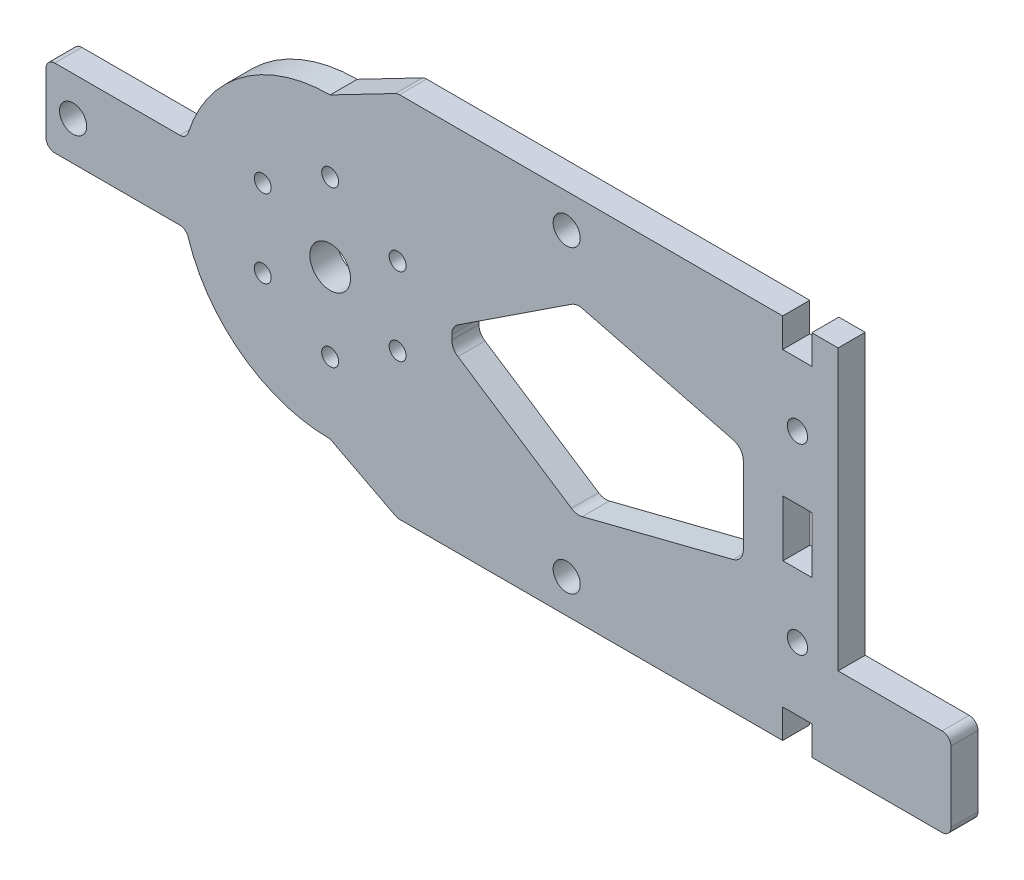
SolidWorks part; units mm, degrees
ref_plane "前视基准面" through (0, 0, 0) normal (0, 0, 1) x (1, 0, 0)
ref_plane "上视基准面" through (0, 0, 0) normal (0, 1, 0) x (1, 0, 0)
ref_plane "右视基准面" through (0, 0, 0) normal (1, 0, 0) x (0, 0, -1)
sketch "草图1" plane through (0, 0, 0) normal (0, 0, 1) x (1, 0, 0)
  line L0 (30.001, 15) -> (30.001, 12) construction
  line L1 (27.8157, 27.15) -> (32.1157, 27.15) construction
  line L2 (32.151, -4.15) -> (27.851, -4.15)
  line L3 (32.151, -4.15) -> (32.151, 4.15)
  line L4 (32.151, 4.15) -> (27.851, 4.15)
  line L5 (27.851, -4.15) -> (27.851, 4.15)
  line L6 (32.151, -4.15) -> (27.851, 4.15) construction
  line L7 (32.151, 4.15) -> (27.851, -4.15) construction
  line L8 (32.1157, 27.15) -> (32.1157, 22.85)
  line L9 (27.8157, 22.85) -> (32.1157, 22.85)
  line L10 (27.8157, 27.15) -> (27.8157, 22.85)
  line L11 (30.001, 0) -> (30.8707, 0) construction
  line L12 (27.8157, -27.15) -> (32.1157, -27.15) construction
  line L13 (30.001, -15) -> (30.001, -12) construction
  line L14 (27.8157, -27.15) -> (27.8157, -22.85)
  line L15 (27.8157, -22.85) -> (32.1157, -22.85)
  line L16 (32.1157, -27.15) -> (32.1157, -22.85)
  line L17 (32.1157, -27.15) -> (36.001, -27.15)
  line L18 (36.001, -27.15) -> (36.001, 27.15) construction
  line L19 (36.001, 27.15) -> (32.1157, 27.15)
  line L23 (-38.999, -22.002) -> (-29.075, -27.15)
  line L25 (-38.999, 22.002) -> (-29.075, 27.15)
  line L29 (27.8157, -27.15) -> (-29.075, -27.15)
  line L30 (-29.075, 27.15) -> (27.8157, 27.15)
  line L31 (-29.075, -27.15) -> (-29.075, 27.15) construction
  line L34 (-48.9583, 5.75) -> (-48.9583, -5.75) construction
  line L38 (-60.2364, 5.75) -> (-80.9583, 5.75)
  line L39 (-80.9583, -5.75) -> (-60.2364, -5.75)
  line L40 (-80.9583, 5.75) -> (-80.9583, -5.75)
  line L41 (36.001, -27.15) -> (52.6592, -27.15)
  line L42 (52.6592, -27.15) -> (52.6592, -14.15)
  line L43 (52.6592, -14.15) -> (36.001, -14.15)
  line L44 (36.001, -14.15) -> (36.001, 27.15)
  line L45 (-4.075, -22.15) -> (30.001, -13.5) construction
  line L46 (30.001, -13.5) -> (30.001, 13.5) construction
  line L47 (30.001, 13.5) -> (-4.075, 22.15) construction
  line L48 (-4.075, 22.15) -> (-29.0397, 5.75) construction
  line L49 (-29.0397, 5.75) -> (-29.0397, -5.75) construction
  line L50 (-29.0397, -5.75) -> (-4.075, -22.15) construction
  line L51 (-21.0397, -1.4336) -> (-2.6278, -13.5289)
  line L52 (-2.6278, -13.5289) -> (22.001, -7.277)
  line L53 (22.001, -7.277) -> (22.001, 7.277)
  line L54 (22.001, 7.277) -> (-2.6278, 13.5289)
  line L55 (-2.6278, 13.5289) -> (-21.0397, 1.4336)
  line L56 (-21.0397, 1.4336) -> (-21.0397, -1.4336)
  circle A0 centre (30.001, 13.5) radius 1.5
  circle A1 centre (30.001, -13.5) radius 1.5
  circle A3 centre (-38.999, 0) radius 3
  circle A6 centre (-38.999, 0) radius 11.5 construction
  circle A7 centre (-38.999, -11.5) radius 1.25
  circle A18 centre (-38.999, 0) radius 22.002 construction
  circle A25 centre (-48.9583, -5.75) radius 1.25
  circle A26 centre (-48.9583, 5.75) radius 1.25
  circle A27 centre (-38.999, 11.5) radius 1.25
  circle A28 centre (-29.0397, 5.75) radius 1.25
  circle A29 centre (-29.0397, -5.75) radius 1.25
  circle A30 centre (-4.075, -22.15) radius 2
  circle A31 centre (-4.075, 22.15) radius 2
  arc A32 (-38.999, -22.002) -> (-60.2364, -5.75) centre (-38.999, 0) cw
  arc A33 (-60.2364, 5.75) -> (-38.999, 22.002) centre (-38.999, 0) cw
  circle A34 centre (-76.9583, 0) radius 2
  point P4 (30.001, 0)
  dimension "D3" = 6
  dimension "D4" = 75
  dimension "D5" = 6
  dimension "D6" = 11.5
  dimension "D7" = 23
  dimension "D8" = 2.5
  dimension "D9" = 25
  dimension "D11" = 5
  dimension "D14" = 4
  dimension "D1" = 8.3
  dimension "D2" = 4.3
  dimension "D10" = 5
  dimension "D12" = 25
  dimension "D13" = 28
  dimension "D15" = 3.8853
  dimension "D16" = 4.3
  dimension "D17" = 13
  dimension "D18" = 8
extrude "凸台-拉伸1" add sketch "草图1" along normal blind 4
fillet "圆角1" radius 1.3 8 edges at (-80.9583, 5.75, 2) (-80.9583, -5.75, 2) (-29.075, 27.15, 2) (-29.075, -27.15, 2) (52.6592, -27.15, 2) (52.6592, -14.15, 2) (-60.2364, 5.75, 2) (-60.2364, -5.75, 2)
fillet "圆角2" radius 2 6 edges at (22.001, 7.277, 2) (22.001, -7.277, 2) (-2.6278, -13.5289, 2) (-2.6278, 13.5289, 2) (-21.0397, 1.4336, 2) (-21.0397, -1.4336, 2)
